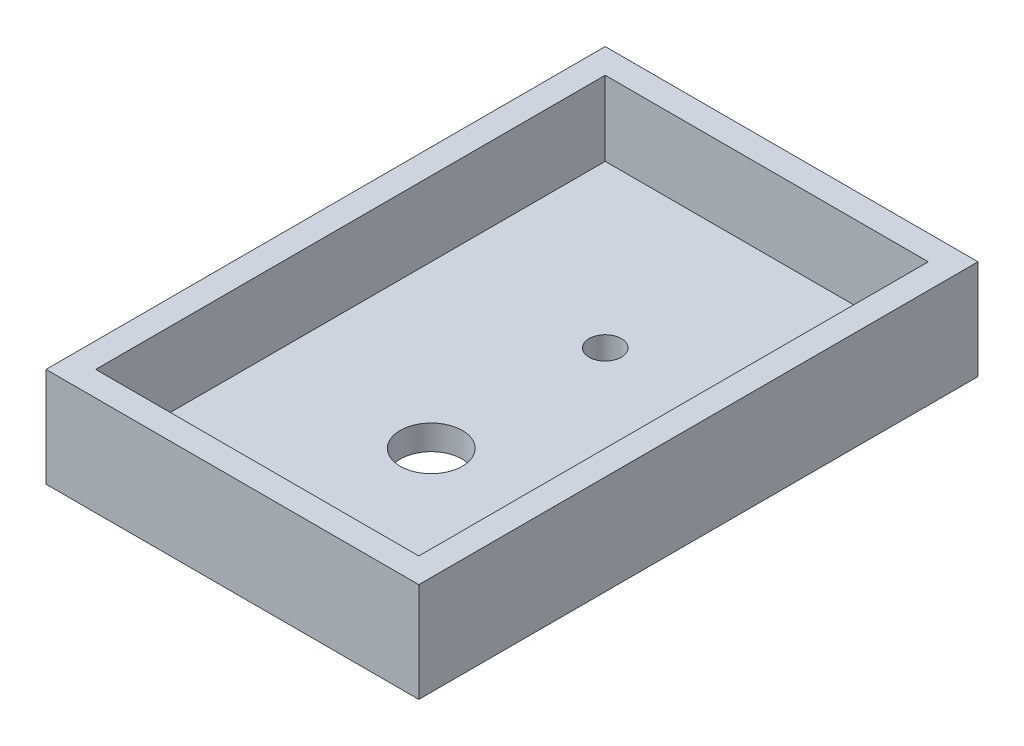
SolidWorks part; units mm, degrees
ref_plane "Front Plane" through (0, 0, 0) normal (0, 0, 1) x (1, 0, 0)
ref_plane "Top Plane" through (0, 0, 0) normal (0, 1, 0) x (1, 0, 0)
ref_plane "Right Plane" through (0, 0, 0) normal (1, 0, 0) x (0, 0, -1)
sketch "Sketch1" plane through (0, 0, 0) normal (0, 1, 0) x (1, 0, 0)
  line L1 (0, 0) -> (38.1, 0)
  line L2 (0, 0) -> (0, 57.15)
  line L3 (0, 57.15) -> (38.1, 57.15)
  line L4 (38.1, 0) -> (38.1, 57.15)
  dimension "D1" = 57.15
  dimension "D2" = 38.1
extrude "Boss-Extrude1" add sketch "Sketch1" along normal blind 10.16
shell "Shell1" thickness 2.54
sketch "Sketch3" plane through (0, 0, 0) normal (0, -1, 0) x (1, 0, 0)
  line L0 (38.1, -57.15) -> (0, -57.15) construction
  line L1 (0, -57.15) -> (0, 0) construction
  circle A0 centre (19.05, -38.1) radius 1.651
  circle A1 centre (19.05, -20.32) radius 3.175
  point P6 (0, 0)
  dimension "D1" = 17.78
  dimension "D3" = 3.302
  dimension "D4" = 6.35
  dimension "D2" = 19.05
  dimension "D5" = 19.05
extrude "Cut-Extrude1" cut sketch "Sketch3" against normal blind 27.94
